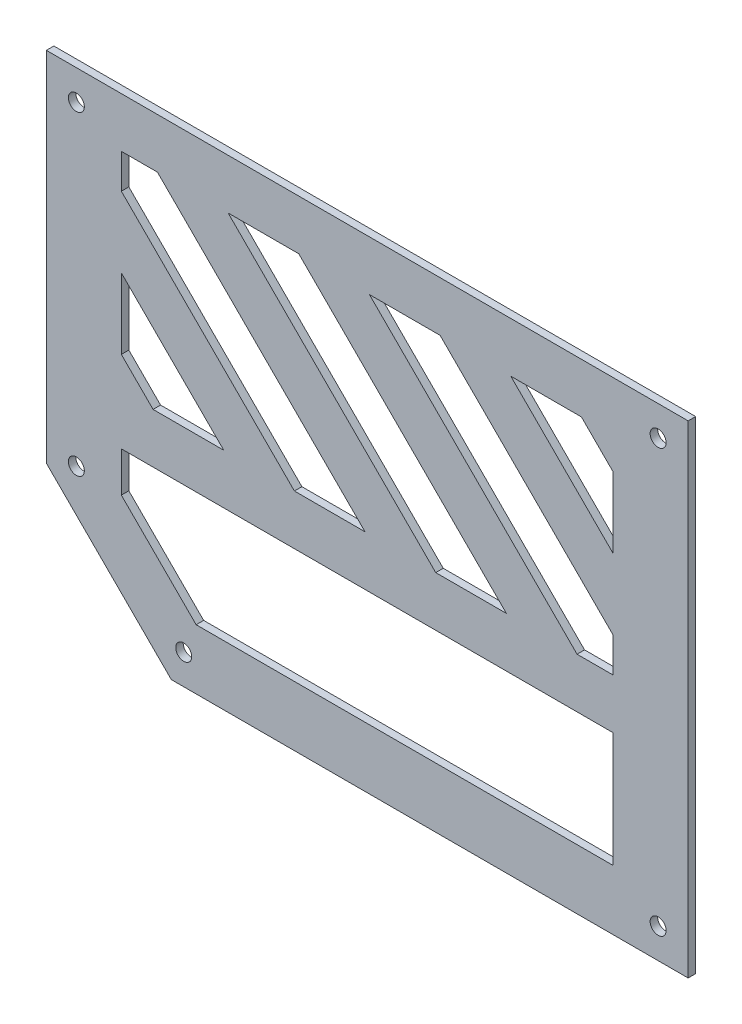
SolidWorks part; units mm, degrees
ref_plane "Front Plane" through (0, 0, 0) normal (0, 0, 1) x (1, 0, 0)
ref_plane "Top Plane" through (0, 0, 0) normal (0, 1, 0) x (1, 0, 0)
ref_plane "Right Plane" through (0, 0, 0) normal (1, 0, 0) x (0, 0, -1)
sketch "Sketch1" plane through (0, 0, 0) normal (0, 0, 1) x (1, 0, 0)
  line L0 (-4.5, 523.53) -> (-4.5, 546.53) construction
  line L1 (-87.9442, 523.53) -> (-4.5, 523.53) construction
  line L2 (-102.9147, 538.5006) -> (-87.9442, 523.53) construction
  line L3 (-102.9147, 546.53) -> (-102.9147, 538.5006) construction
  line L4 (-4.5, 546.53) -> (-102.9147, 546.53) construction
  line L5 (-117.9147, 608.0809) -> (-117.9147, 536.53)
  line L6 (-117.9147, 536.53) -> (-92.9147, 511.53)
  line L7 (-92.9147, 511.53) -> (10.5, 511.53)
  line L8 (10.5, 511.53) -> (10.5, 608.0809)
  line L9 (10.5, 608.0809) -> (-117.9147, 608.0809)
  line L10 (-117.9147, 608.0809) -> (-117.9147, 536.53)
  line L11 (-117.9147, 536.53) -> (-92.9147, 511.53)
  line L12 (-92.9147, 511.53) -> (10.5, 511.53)
  line L13 (10.5, 511.53) -> (10.5, 608.0809)
  line L14 (10.5, 608.0809) -> (-117.9147, 608.0809)
  line L15 (-4.5, 523.53) -> (-4.5, 546.53)
  line L16 (-87.9442, 523.53) -> (-4.5, 523.53)
  line L17 (-102.9147, 538.5006) -> (-87.9442, 523.53)
  line L18 (-102.9147, 546.53) -> (-102.9147, 538.5006)
  line L19 (-4.5, 546.53) -> (-102.9147, 546.53)
  dimension "D1" = 0
extrude "Boss-Extrude1" add sketch "Sketch1" along normal blind 1.5
sketch "Sketch2" plane through (0, 0, 1.5) normal (0, 0, 1) x (1, 0, 0)
  line L0 (10.5, 608.0809) -> (-117.9147, 608.0809) construction
  line L1 (-111.9147, 602.0809) -> (4.5, 602.0809) construction
  line L2 (-111.9147, 602.0809) -> (-111.9147, 517.53) construction
  line L3 (-111.9147, 517.53) -> (4.5, 517.53) construction
  line L4 (4.5, 602.0809) -> (4.5, 517.53) construction
  line L5 (-117.9147, 608.0809) -> (-117.9147, 536.53) construction
  line L6 (10.5, 511.53) -> (10.5, 608.0809) construction
  line L7 (-92.9147, 511.53) -> (10.5, 511.53) construction
  line L8 (-111.9147, 539.0153) -> (-90.4295, 517.53) construction
  line L9 (-117.9147, 536.53) -> (-92.9147, 511.53) construction
  circle A0 centre (-111.9147, 539.0153) radius 1.6
  circle A1 centre (-90.4295, 517.53) radius 1.6
  circle A2 centre (-111.9147, 602.0809) radius 1.6
  circle A3 centre (4.5, 602.0809) radius 1.6
  circle A4 centre (4.5, 517.53) radius 1.6
  dimension "D5" = 3.2
  dimension "D1" = 6
  dimension "D2" = 6
  dimension "D3" = 6
  dimension "D4" = 6
  dimension "D6" = 6
extrude "Cut-Extrude1" cut sketch "Sketch2" against normal blind 3.5
sketch "Sketch3" plane through (0, 0, 1.5) normal (0, 0, 1) x (1, 0, 0)
  line L0 (-102.9147, 546.53) -> (-102.9147, 538.5006) construction
  line L1 (-102.9147, 598.0809) -> (-4.5, 598.0809)
  line L2 (-102.9147, 598.0809) -> (-102.9147, 556.53)
  line L3 (-102.9147, 556.53) -> (-4.5, 556.53)
  line L4 (-4.5, 598.0809) -> (-4.5, 556.53)
  line L5 (-102.9147, 556.53) -> (-99.7383, 559.7064) construction
  line L6 (-4.5, 523.53) -> (-4.5, 546.53) construction
  line L7 (10.5, 608.0809) -> (-117.9147, 608.0809) construction
  line L8 (-4.5, 546.53) -> (-102.9147, 546.53) construction
  line L9 (-180.3188, 612.0069) -> (-166.1788, 612.0069)
  line L10 (-180.3188, 612.0069) -> (-104.8711, 536.5592)
  line L11 (-166.1788, 612.0069) -> (-90.7311, 536.5592)
  line L12 (-104.8711, 536.5592) -> (-90.7311, 536.5592)
  line L13 (-152.0388, 612.0069) -> (-137.8988, 612.0069)
  line L14 (-152.0388, 612.0069) -> (-76.5911, 536.5592)
  line L15 (-137.8988, 612.0069) -> (-62.4511, 536.5592)
  line L16 (-76.5911, 536.5592) -> (-62.4511, 536.5592)
  line L17 (-123.7588, 612.0069) -> (-109.6188, 612.0069)
  line L18 (-123.7588, 612.0069) -> (-48.3111, 536.5592)
  line L19 (-109.6188, 612.0069) -> (-34.1711, 536.5592)
  line L20 (-48.3111, 536.5592) -> (-34.1711, 536.5592)
  line L21 (-95.4788, 612.0069) -> (-81.3388, 612.0069)
  line L22 (-95.4788, 612.0069) -> (-20.0311, 536.5592)
  line L23 (-81.3388, 612.0069) -> (-5.8911, 536.5592)
  line L24 (-20.0311, 536.5592) -> (-5.8911, 536.5592)
  line L25 (-67.1988, 612.0069) -> (-53.0588, 612.0069)
  line L26 (-67.1988, 612.0069) -> (8.2489, 536.5592)
  line L27 (-53.0588, 612.0069) -> (22.3889, 536.5592)
  line L28 (8.2489, 536.5592) -> (22.3889, 536.5592)
  line L29 (-38.9188, 612.0069) -> (-24.7788, 612.0069)
  line L30 (-38.9188, 612.0069) -> (36.5289, 536.5592)
  line L31 (-24.7788, 612.0069) -> (50.6689, 536.5592)
  line L32 (36.5289, 536.5592) -> (50.6689, 536.5592)
  line L33 (-10.6388, 612.0069) -> (3.5012, 612.0069)
  line L34 (-10.6388, 612.0069) -> (64.8089, 536.5592)
  line L35 (3.5012, 612.0069) -> (78.9489, 536.5592)
  line L36 (64.8089, 536.5592) -> (78.9489, 536.5592)
  line L37 (-4.5, 598.0809) -> (-7.6764, 594.9045) construction
  dimension "D1" = 10
  dimension "D2" = 10
  dimension "D3" = 135
  dimension "D4" = 14.14
  dimension "D6" = 14.14
  dimension "D5" = 7
extrude "Cut-Extrude3" cut sketch "Sketch3" against normal blind 10 contours L15 L2 L14 L3 | L19 L1 L2 L18 L3 | L23 L1 L22 L3 | L27 L1 L26 L3 L4 | L31 L1 L30 L4
